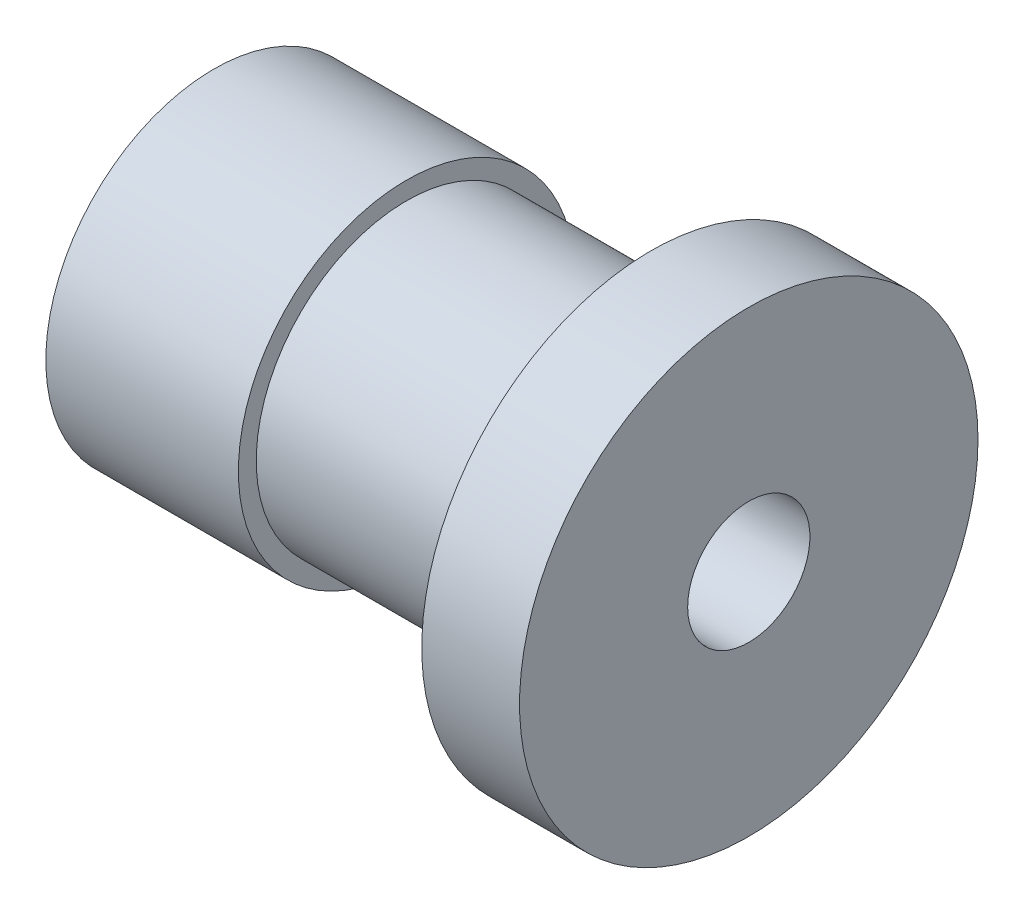
SolidWorks part; units mm, degrees
ref_plane "Front Plane" through (0, 0, 0) normal (0, 0, 1) x (1, 0, 0)
ref_plane "Top Plane" through (0, 0, 0) normal (0, 1, 0) x (1, 0, 0)
ref_plane "Right Plane" through (0, 0, 0) normal (1, 0, 0) x (0, 0, -1)
sketch "Sketch1" plane through (0, 0, 0) normal (1, 0, 0) x (0, 0, -1)
  circle A0 centre (0, 0) radius 5.5
extrude "Boss-Extrude1" add sketch "Sketch1" along normal blind 6.3
sketch "Sketch2" plane through (6.3, 0, 0) normal (1, 0, 0) x (0, 0, -1)
  circle A0 centre (0, 0) radius 4.915
  dimension "D1" = 9.83
extrude "Boss-Extrude2" add sketch "Sketch2" along normal blind 8
sketch "Sketch3" plane through (14.3, 0, 0) normal (1, 0, 0) x (0, 0, -1)
  circle A0 centre (0, 0) radius 7.5
  dimension "D1" = 15
extrude "Boss-Extrude3" add sketch "Sketch3" along normal blind 3.2
sketch "Sketch5" plane through (0, 0, 0) normal (-1, 0, 0) x (0, 0, 1)
  circle A0 centre (0, 0) radius 2
  dimension "D1" = 4
extrude "Cut-Extrude1" cut sketch "Sketch5" against normal through all
